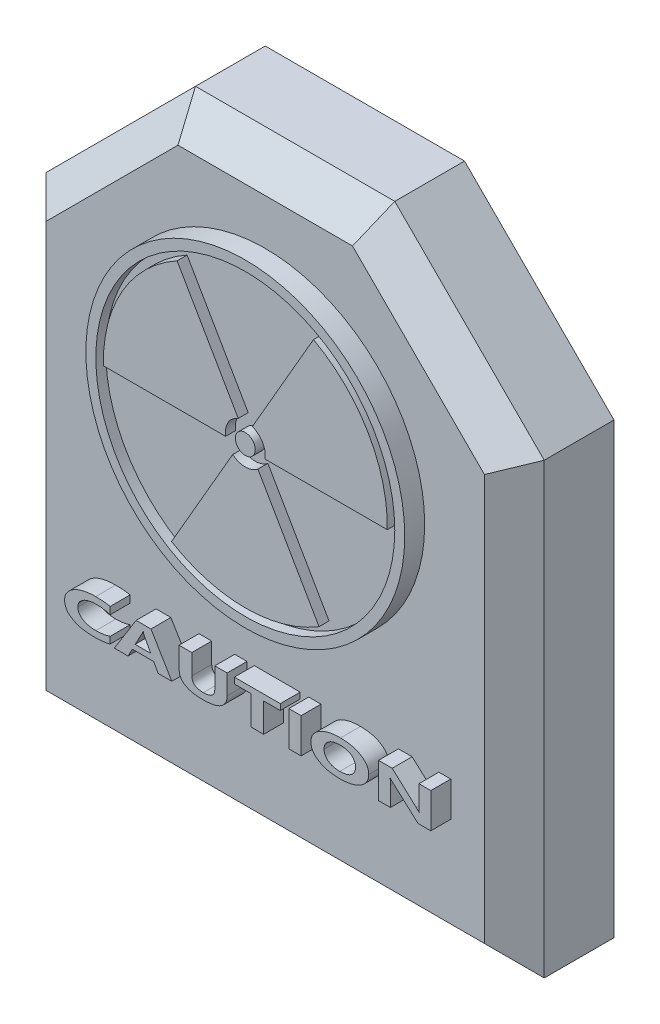
SolidWorks part; units mm, degrees
ref_plane "前视基准面" through (0, 0, 0) normal (0, 0, 1) x (1, 0, 0)
ref_plane "上视基准面" through (0, 0, 0) normal (0, 1, 0) x (1, 0, 0)
ref_plane "右视基准面" through (0, 0, 0) normal (1, 0, 0) x (0, 0, -1)
sketch "草图1" plane through (0, 0, 0) normal (0, 0, 1) x (1, 0, 0)
  line L0 (-25, 20) -> (-21.2132, 23.7868)
  line L1 (-25, -30) -> (25, -30)
  line L2 (-25, -30) -> (-25, 15)
  line L3 (-10, 30) -> (10, 30)
  line L4 (25, -30) -> (25, 15)
  line L5 (-25, -30) -> (25, 30) construction
  line L6 (-25, 30) -> (25, -30) construction
  line L8 (-25, 15) -> (-10, 30)
  line L9 (25, 15) -> (10, 30)
  point P0 (0, 0)
  point P12 (-25, 30)
  point P15 (25, 30)
  point P17 (-10.6066, 34.3934)
  point P18 (0, 45)
  dimension "D1" = 50
  dimension "D2" = 60
extrude "凸台-拉伸1" add sketch "草图1" along normal blind 10 contours L4 L9 L3 L8 L2 L1
chamfer "倒角2" distance 3 angle 45 6 edges at (0, -30, 10) (-25, -7.5, 10) (-17.5, 22.5, 10) (0, 30, 10) (17.5, 22.5, 10) (25, -7.5, 10)
sketch "草图2" plane through (0, 0, 10) normal (0, 0, 1) x (1, 0, 0)
  line L0 (0, -5.5) -> (0, 5.5) construction
  circle A0 centre (0, 6.4099) radius 16
  point P4 (0, 3.0189)
  point P5 (0, 6.4099)
extrude "凸台-拉伸2" add sketch "草图2" along normal blind 2
sketch "草图5" plane through (0, 0, 12) normal (0, 0, 1) x (1, 0, 0)
  circle A0 centre (0, 6.4099) radius 15
extrude "切除-拉伸4" cut sketch "草图5" against normal blind 1
sketch "草图6" plane through (0, 0, 11) normal (0, 0, 1) x (1, 0, 0)
  circle A0 centre (0, 6.4099) radius 1
extrude "凸台-拉伸3" add sketch "草图6" along normal blind 1
sketch "草图7" plane through (0, 0, 11) normal (0, 0, 1) x (1, 0, 0)
  line L0 (0, 4.4099) -> (0, -7.8392) construction
  line L1 (-1.2657, 4.8614) -> (-7.4015, -5.7661)
  line L2 (1.2657, 4.8614) -> (7.4015, -5.7661)
  line L3 (-1.9739, 6.0881) -> (-14.2455, 6.0881)
  line L4 (-0.7082, 8.2803) -> (-6.844, 18.9078)
  line L5 (0.7082, 8.2803) -> (6.844, 18.9078)
  line L6 (1.9739, 6.0881) -> (14.2455, 6.0881)
  arc A0 (-1.2657, 4.8614) -> (1.2657, 4.8614) centre (0, 6.4099) ccw
  arc A1 (-7.4015, -5.7661) -> (7.4015, -5.7661) centre (0, 6.4099) ccw
  arc A2 (-0.7082, 8.2803) -> (-1.9739, 6.0881) centre (0, 6.4099) ccw
  arc A3 (-6.844, 18.9078) -> (-14.2455, 6.0881) centre (0, 6.4099) ccw
  arc A4 (1.9739, 6.0881) -> (0.7082, 8.2803) centre (0, 6.4099) ccw
  arc A5 (14.2455, 6.0881) -> (6.844, 18.9078) centre (0, 6.4099) ccw
  point P19 (0, 6.4099)
  dimension "D1" = 4
  dimension "D2" = 28.4982
  dimension "D3" = 30
  dimension "D5" = 12.2715
  dimension "D4" = 3
extrude "凸台-拉伸4" add sketch "草图7" along normal blind 1
sketch "草图8" plane through (0, 0, 10) normal (0, 0, 1) x (1, 0, 0)
  text T0 "CAUTION" font "微软雅黑" height 3.5
extrude "凸台-拉伸5" add sketch "草图8" along normal blind 2
